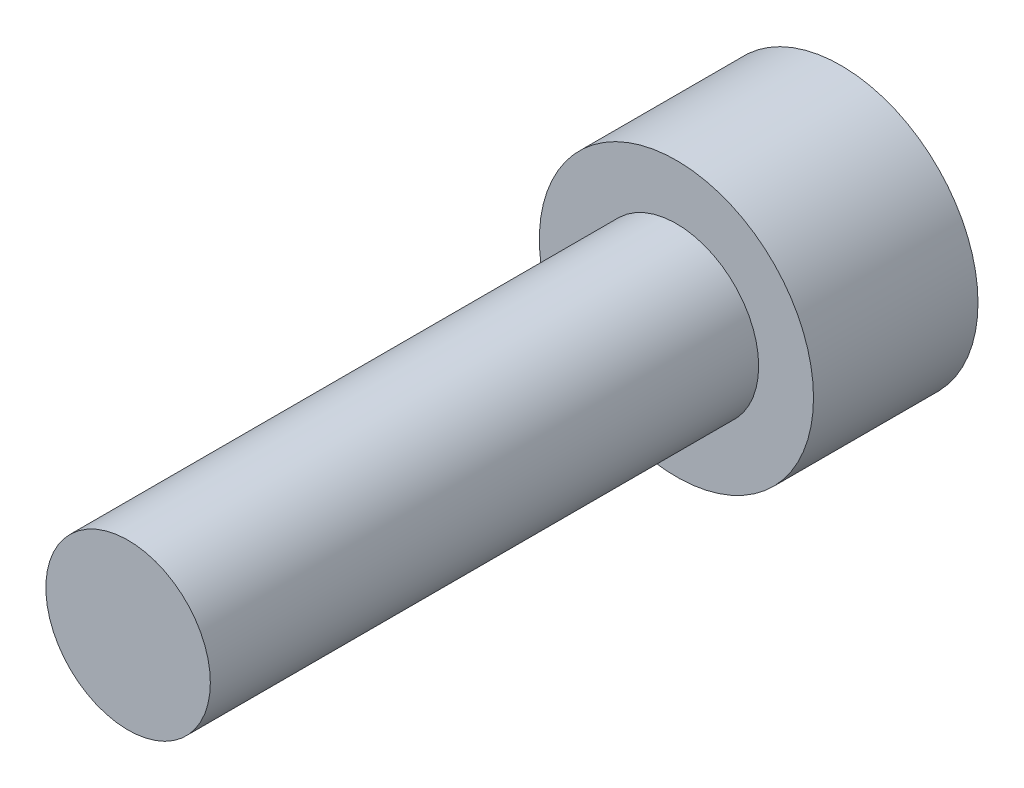
SolidWorks part; units mm, degrees
ref_plane "正面" through (0, 0, 0) normal (0, 0, 1) x (1, 0, 0)
ref_plane "平面" through (0, 0, 0) normal (0, 1, 0) x (1, 0, 0)
ref_plane "右側面" through (0, 0, 0) normal (1, 0, 0) x (0, 0, -1)
sketch "ｽｹｯﾁ1" plane through (0, 0, 0) normal (0, 0, 1) x (1, 0, 0)
  circle A0 centre (0, 0) radius 5
  dimension "D1" = 10
extrude "ﾎﾞｽ - 押し出し1" add sketch "ｽｹｯﾁ1" along normal blind 6
sketch "ｽｹｯﾁ2" plane through (0, 0, 6) normal (0, 0, 1) x (1, 0, 0)
  circle A0 centre (0, 0) radius 3
  dimension "D1" = 6
extrude "ﾎﾞｽ - 押し出し2" add sketch "ｽｹｯﾁ2" along normal blind 20
cosmetic thread "ねじ山1" parameters "D2"=5
sketch "ｽｹｯﾁ3" plane through (0, 0, 0) normal (0, 0, -1) x (-1, 0, 0)
  line L1 (2.4446, 2.3616) -> (-0.8229, 3.2979)
  line L2 (-0.8229, 3.2979) -> (-3.2675, 0.9363)
  line L3 (-3.2675, 0.9363) -> (-2.4446, -2.3616)
  line L4 (-2.4446, -2.3616) -> (0.8229, -3.2979)
  line L5 (0.8229, -3.2979) -> (3.2675, -0.9363)
  line L6 (3.2675, -0.9363) -> (2.4446, 2.3616)
  circle A0 centre (0, 0) radius 2.9436 construction
extrude "ｶｯﾄ - 押し出し1" cut sketch "ｽｹｯﾁ3" against normal blind 3
